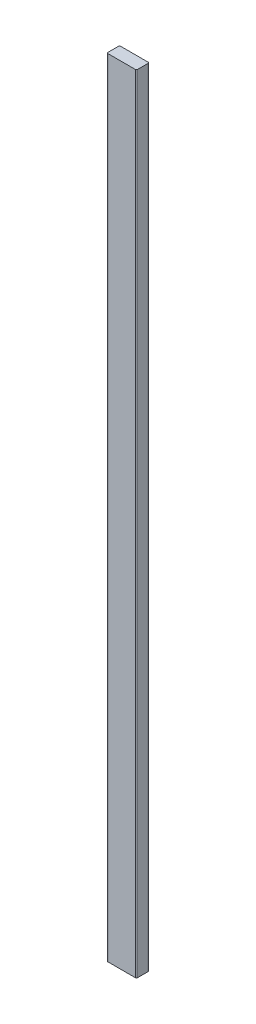
SolidWorks part; units mm, degrees
ref_plane "Front" through (0, 0, 0) normal (0, 0, 1) x (1, 0, 0)
ref_plane "Top" through (0, 0, 0) normal (0, 1, 0) x (1, 0, 0)
ref_plane "Right" through (0, 0, 0) normal (1, 0, 0) x (0, 0, -1)
sketch "Sketch1" plane through (0, 0, 0) normal (0, 1, 0) x (1, 0, 0)
  line L1 (44.45, 19.05) -> (-44.45, 19.05)
  line L2 (44.45, 19.05) -> (44.45, -19.05)
  line L3 (44.45, -19.05) -> (-44.45, -19.05)
  line L4 (-44.45, 19.05) -> (-44.45, -19.05)
  line L5 (44.45, 19.05) -> (-44.45, -19.05) construction
  line L6 (44.45, -19.05) -> (-44.45, 19.05) construction
  point P0 (0, 0)
  dimension "D1" = 38.1
  dimension "D2" = 88.9
extrude "Boss-Extrude1" add sketch "Sketch1" along normal blind 2362.2
ref_plane "Plane1" [suppressed] through (0, 1181.1, 0) normal (0, -1, 0) x (-1, 0, 0)
hole_wizard "1/4 (0.25) Diameter Hole1" [suppressed] positions "Sketch3" profile "Sketch4" hole size "1/4" standard "ANSI Inch"
sketch "Sketch3" plane through (0, 0, -19.05) normal (0, 0, -1) x (-1, 0, 0)
  line L0 (-44.45, 0) -> (44.45, 0) construction
  line L1 (-20.955, 1181.1) -> (20.955, 1181.1) construction
  point P0 (0, 88.9)
  point P12 (0, 0)
  point P30 (0, 434.975)
  point P31 (0, 781.05)
  point P32 (0, 1127.125)
  dimension "D1" = 53.975
  dimension "D2" = 4
sketch "Sketch4" plane through (0, 88.9, -19.05) normal (1, 0, 0) x (0, 1, 0)
  line L0 (0, 0) -> (0, 38.1)
  line L1 (0, 38.1) -> (3.175, 38.1)
  line L2 (3.175, 38.1) -> (3.175, 0)
  line L5 (3.175, 0) -> (0, 0)
  line L11 (0, -6.35) -> (0, 107.95) construction
  dimension "Thru Hole Dia." = 6.35
  dimension "Thru Hole Depth" = 38.1
fillet "Fillet1" radius 3.175 4 edges at (-44.45, 1181.1, 19.05) (-44.45, 1181.1, -19.05) (44.45, 1181.1, 19.05) (44.45, 1181.1, -19.05)
mirror "Mirror1" [suppressed] about plane through (0, 1181.1, 0) normal (0, -1, 0)
